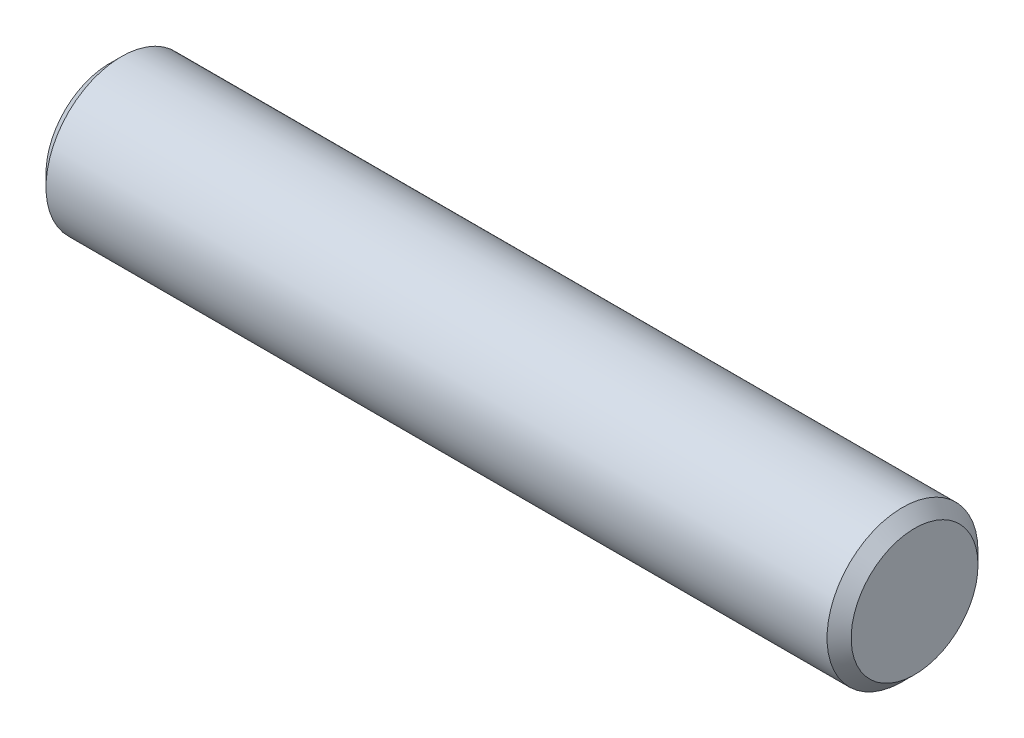
SolidWorks part; units mm, degrees
material "AISI 304"
ref_plane "Front" through (0, 0, 0) normal (0, 0, 1) x (1, 0, 0)
ref_plane "Top" through (0, 0, 0) normal (0, 1, 0) x (1, 0, 0)
ref_plane "Right" through (0, 0, 0) normal (1, 0, 0) x (0, 0, -1)
sketch "Sketch1" plane through (0, 0, 0) normal (1, 0, 0) x (0, 0, -1)
  circle A0 centre (0, 0) radius 2.3812
  dimension "D1" = 4.7625
extrude "Extrude1" add sketch "Sketch1" along normal blind 25.4
chamfer "Chamfer1" distance 0.381 angle 45 2 edges at (0, 0, -2.3812) (25.4, 0, -2.3812)
